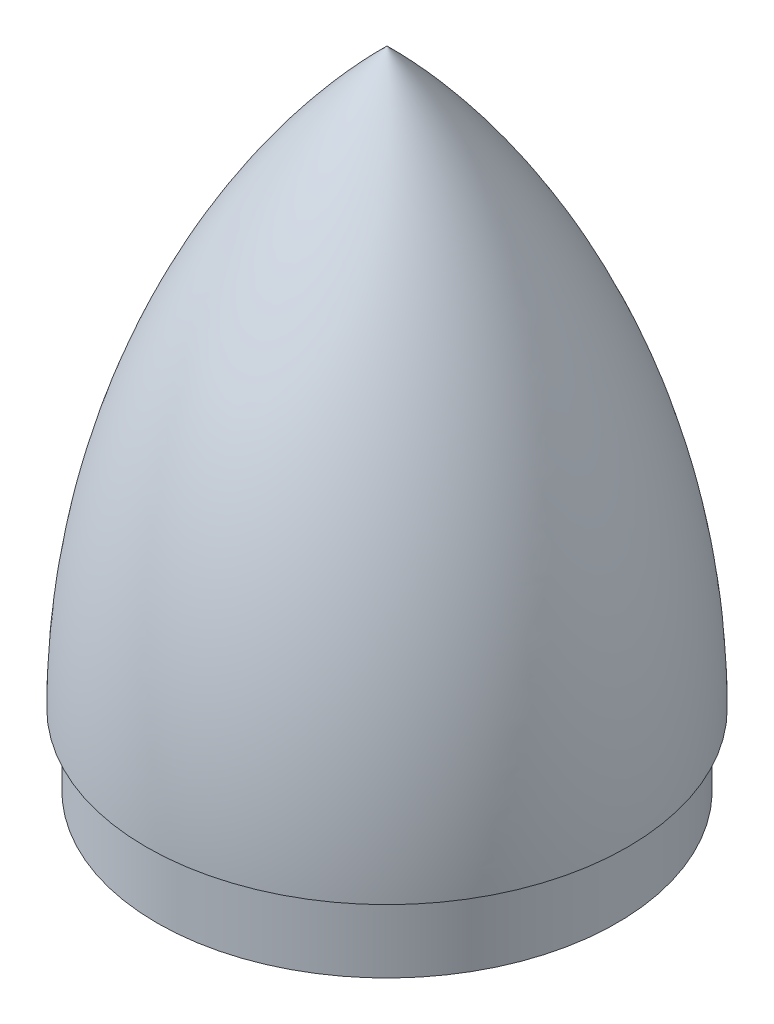
SolidWorks part; units mm, degrees
ref_plane "Front Plane" through (0, 0, 0) normal (1, 0, 0) x (0, 1, 0)
ref_plane "Top Plane" through (0, 0, 0) normal (0, 0, 1) x (0, 1, 0)
ref_plane "Right Plane" through (0, 0, 0) normal (0, 1, 0) x (-1, 0, 0)
sketch "Sketch1" plane through (0, 0, 0) normal (0, 0, 1) x (0, 1, 0)
  line L1 (0, 41.1) -> (12.7, 41.1)
  line L2 (12.7, 41.1) -> (12.7, 43)
  line L4 (0, 40.1) -> (13.7, 40.1)
  line L7 (115.2, 0) -> (113.7936, 0)
  line L8 (-1000, 0) -> (49000, 0) construction
  line L9 (13.7, 40.1) -> (35.906, 40.1)
  line L10 (-0.0805, 41.0968) -> (-0.2014, 41.1) construction
  line L11 (13.7, 40.1) -> (13.7, 41.9965) construction
  line L12 (0, 40.1) -> (0, 40.1) construction
  line L13 (0, 40.1) -> (0, 41.1)
  line L14 (-0.2014, 41.1) -> (12.7, 41.1) construction
  arc A0 (12.7, 43) -> (115.2, 0) centre (12.7, -100.6657) cw
  arc A1 (35.906, 40.1) -> (113.7936, 0) centre (12.7, -100.6657) cw
  arc A2 (13.7, 41.9965) -> (114.4865, -0.7007) centre (12.7, -100.6657) cw construction
  point P0 (110.9019, 0)
  dimension "D1" = 86
  dimension "D2" = 1
  dimension "D3" = 82.2
  dimension "D4" = 12.7
  dimension "D5" = 102.5
revolve "Revolve1" add sketch "Sketch1" angle 360 about L8
